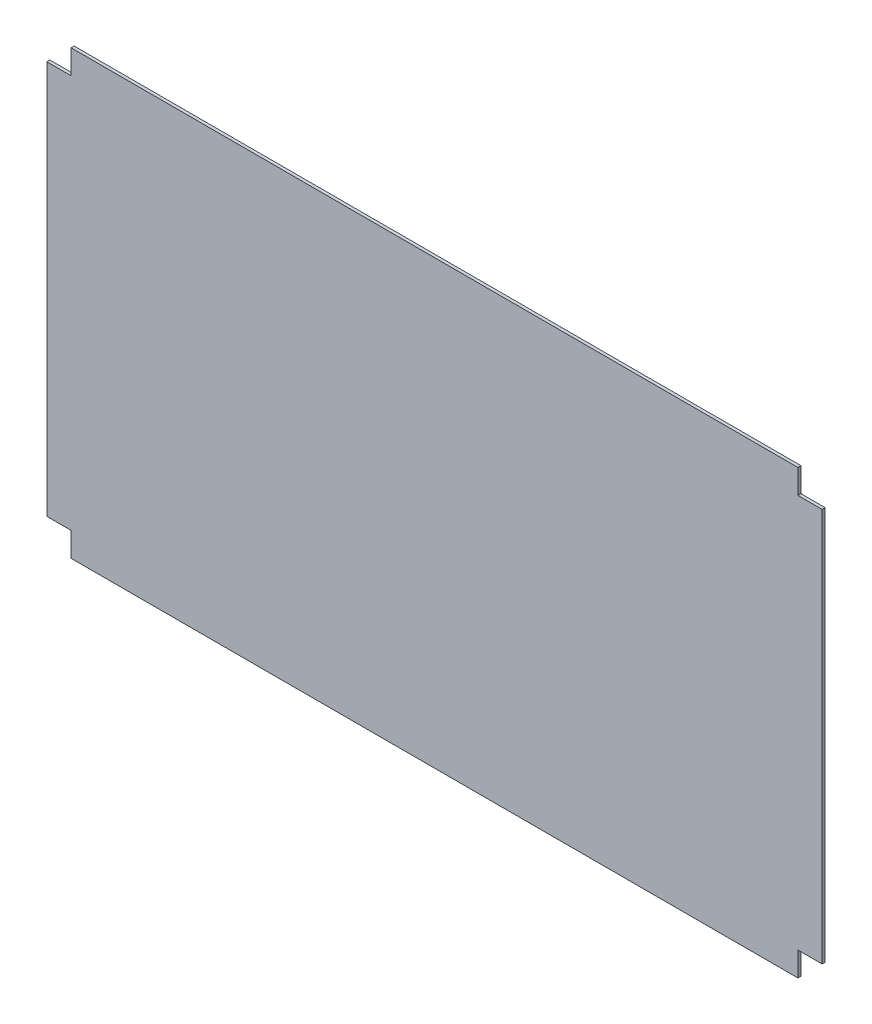
SolidWorks part; units mm, degrees
ref_plane "Plan de face" through (0, 0, 0) normal (0, 0, 1) x (1, 0, 0)
ref_plane "Plan de dessus" through (0, 0, 0) normal (0, 1, 0) x (1, 0, 0)
ref_plane "Plan de droite" through (0, 0, 0) normal (1, 0, 0) x (0, 0, -1)
sketch "Esquisse1" plane through (0, 0, 0) normal (0, 0, 1) x (1, 0, 0)
  line L1 (0, 0) -> (1280, 0)
  line L2 (0, 0) -> (0, -730)
  line L3 (0, -730) -> (1280, -730)
  line L4 (1280, 0) -> (1280, -730)
  line L5 (0, 0) -> (40, 0)
  line L6 (0, 0) -> (0, -40)
  line L7 (0, -40) -> (40, -40)
  line L8 (40, 0) -> (40, -40)
  line L9 (1280, 0) -> (1240, 0)
  line L10 (1280, 0) -> (1280, -40)
  line L11 (1280, -40) -> (1240, -40)
  line L12 (1240, 0) -> (1240, -40)
  line L13 (1280, -730) -> (1240, -730)
  line L14 (1280, -730) -> (1280, -690)
  line L15 (1280, -690) -> (1240, -690)
  line L16 (1240, -730) -> (1240, -690)
  line L17 (0, -730) -> (40, -730)
  line L18 (0, -730) -> (0, -690)
  line L19 (0, -690) -> (40, -690)
  line L20 (40, -730) -> (40, -690)
  dimension "D1" = 40
  dimension "D2" = 1280
  dimension "D3" = 730
  dimension "D4" = 40
  dimension "D5" = 40
  dimension "D6" = 40
  dimension "D7" = 40
  dimension "D8" = 40
  dimension "D9" = 40
  dimension "D10" = 40
extrude "Boss.-Extru.1" add sketch "Esquisse1" along normal blind 5 contours L20 L3 L16 L15 L4 L11 L12 L1 L8 L7 L2 L19
